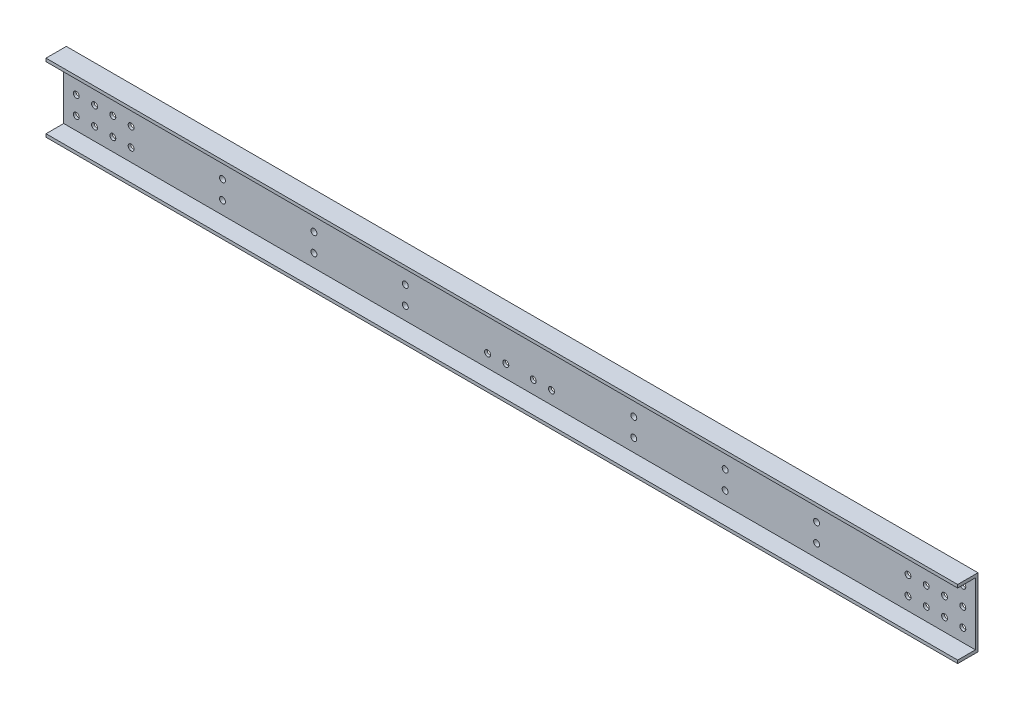
SolidWorks part; units mm, degrees
ref_plane "前视" through (0, 0, 0) normal (0, 0, 1) x (1, 0, 0)
ref_plane "上视" through (0, 0, 0) normal (0, 1, 0) x (1, 0, 0)
ref_plane "右视" through (0, 0, 0) normal (1, 0, 0) x (0, 0, -1)
sketch "草图1" plane through (0, 0, 0) normal (0, 0, 1) x (1, 0, 0)
  line L0 (-253.2778, 0) -> (2143.7198, 0) construction
  line L1 (0, 293.7967) -> (0, -293.7967) construction
  line L2 (1484.3386, 80) -> (1995, 80) construction
  line L3 (-1995, 150) -> (1995, 150)
  line L4 (-1995, 150) -> (-1995, -150)
  line L5 (-1995, -150) -> (1995, -150)
  line L6 (1995, 150) -> (1995, -150)
  line L7 (1940, 137.9179) -> (1940, -34.3032) construction
  line L8 (1860, 137.9179) -> (1860, -34.3032) construction
  line L9 (1780, -27.7215) -> (1780, 137.9179) construction
  line L10 (1700, 137.9179) -> (1700, -27.7215) construction
  line L11 (24.2318, 80) -> (382.2761, 80) construction
  line L12 (60, 137.9179) -> (60, -34.3032) construction
  line L13 (140, -34.3032) -> (140, 137.9179) construction
  circle A0 centre (1940, 0) radius 13
  circle A1 centre (1860, 0) radius 13
  circle A2 centre (1780, 0) radius 13
  circle A3 centre (1700, 0) radius 13
  circle A4 centre (1700, 80) radius 13
  circle A5 centre (1780, 80) radius 13
  circle A6 centre (1860, 80) radius 13
  circle A7 centre (1940, 80) radius 13
  circle A8 centre (1940, -80) radius 13
  circle A9 centre (1860, -80) radius 13
  circle A10 centre (1780, -80) radius 13
  circle A11 centre (1700, -80) radius 13
  circle A12 centre (-1700, -80) radius 13
  circle A13 centre (-1780, -80) radius 13
  circle A14 centre (-1860, -80) radius 13
  circle A15 centre (-1940, -80) radius 13
  circle A16 centre (-1940, 80) radius 13
  circle A17 centre (-1860, 80) radius 13
  circle A18 centre (-1780, 80) radius 13
  circle A19 centre (-1700, 80) radius 13
  circle A20 centre (-1700, 0) radius 13
  circle A21 centre (-1780, 0) radius 13
  circle A22 centre (-1860, 0) radius 13
  circle A23 centre (-1940, 0) radius 13
  circle A24 centre (60, 80) radius 13
  circle A25 centre (140, 80) radius 13
  circle A28 centre (140, -80) radius 13
  circle A29 centre (60, -80) radius 13
  circle A30 centre (-60, -80) radius 13
  circle A31 centre (-140, -80) radius 13
  circle A34 centre (-140, 80) radius 13
  circle A35 centre (-60, 80) radius 13
  dimension "D8" = 26
  dimension "D11" = 26
  dimension "D1" = 300
  dimension "D2" = 3990
  dimension "D3" = 80
  dimension "D4" = 55
  dimension "D5" = 80
  dimension "D6" = 80
  dimension "D7" = 80
  dimension "D9" = 60
  dimension "D10" = 80
extrude "基体-拉伸" add sketch "草图1" along normal blind 11.5
sketch "草图2" plane through (0, 0, 11.5) normal (0, 0, 1) x (1, 0, 0)
  line L0 (1995, -150) -> (1995, 150) construction
  line L1 (-1995, 150) -> (1995, 150)
  line L2 (-1995, 150) -> (-1995, 136.5)
  line L3 (-1995, 136.5) -> (1995, 136.5)
  line L4 (1995, 150) -> (1995, 136.5)
  line L5 (-335.9089, 0) -> (412.8346, 0) construction
  line L6 (1995, -150) -> (1995, -136.5)
  line L7 (-1995, -136.5) -> (1995, -136.5)
  line L8 (-1995, -150) -> (-1995, -136.5)
  line L9 (-1995, -150) -> (1995, -150)
  dimension "D1" = 13.5
extrude "凸台-拉伸1" add sketch "草图2" along normal blind 77.5
sketch "草图3" plane through (0, 0, 0) normal (0, 0, -1) x (-1, 0, 0)
  line L0 (-1674.4159, 0) -> (305.1386, 0) construction
  line L1 (0, 210.2636) -> (0, -302.5744) construction
  line L2 (-1995, -150) -> (-1995, 150) construction
  line L3 (-1335, 115) -> (-1265, 115)
  line L4 (-1335, 115) -> (-1335, -115)
  line L5 (-1335, -115) -> (-1265, -115)
  line L6 (-1265, 115) -> (-1265, -115)
  line L7 (-935, 115) -> (-865, 115)
  line L8 (-935, 115) -> (-935, -115)
  line L9 (-935, -115) -> (-865, -115)
  line L10 (-865, 115) -> (-865, -115)
  line L11 (-535, 115) -> (-465, 115)
  line L12 (-535, 115) -> (-535, -115)
  line L13 (-535, -115) -> (-465, -115)
  line L14 (-465, 115) -> (-465, -115)
  line L15 (465, 115) -> (465, -115)
  line L16 (535, -115) -> (465, -115)
  line L17 (535, 115) -> (535, -115)
  line L18 (535, 115) -> (465, 115)
  line L19 (865, 115) -> (865, -115)
  line L20 (935, -115) -> (865, -115)
  line L21 (935, 115) -> (935, -115)
  line L22 (935, 115) -> (865, 115)
  line L23 (1265, 115) -> (1265, -115)
  line L24 (1335, -115) -> (1265, -115)
  line L25 (1335, 115) -> (1335, -115)
  line L26 (1335, 115) -> (1265, 115)
  dimension "D1" = 70
  dimension "D2" = 70
  dimension "D3" = 70
  dimension "D4" = 230
  dimension "D5" = 660
  dimension "D6" = 400
  dimension "D7" = 400
extrude "凸台-拉伸2" add sketch "草图3" along normal blind 16
sketch "草图4" plane through (0, 0, -16) normal (0, 0, -1) x (-1, 0, 0)
  line L0 (0, 492.3244) -> (0, -548.7366) construction
  line L1 (-500, 124.929) -> (-500, -60.2993) construction
  line L2 (-1300, 124.929) -> (-1300, -60.2993) construction
  line L3 (-900, -60.2993) -> (-900, 236.5151) construction
  line L5 (-1594.4016, 80) -> (-322.6426, 80) construction
  line L6 (-1995, -150) -> (-1995, 150) construction
  line L7 (0, 0) -> (-1594.4016, 0) construction
  circle A0 centre (-1300, 0) radius 13
  circle A1 centre (-1300, 80) radius 13
  circle A2 centre (-900, 80) radius 13
  circle A3 centre (-900, 0) radius 13
  circle A4 centre (-500, 80) radius 13
  circle A5 centre (-500, 0) radius 13
  circle A6 centre (-500, -80) radius 13
  circle A7 centre (-900, -80) radius 13
  circle A8 centre (-1300, -80) radius 13
  circle A9 centre (1300, -80) radius 13
  circle A10 centre (900, -80) radius 13
  circle A11 centre (500, -80) radius 13
  circle A12 centre (500, 0) radius 13
  circle A13 centre (500, 80) radius 13
  circle A14 centre (900, 0) radius 13
  circle A15 centre (900, 80) radius 13
  circle A16 centre (1300, 80) radius 13
  circle A17 centre (1300, 0) radius 13
  dimension "D5" = 26
  dimension "D1" = 695
  dimension "D2" = 400
  dimension "D3" = 400
  dimension "D4" = 80
extrude "切除-拉伸1" cut sketch "草图4" against normal through all
